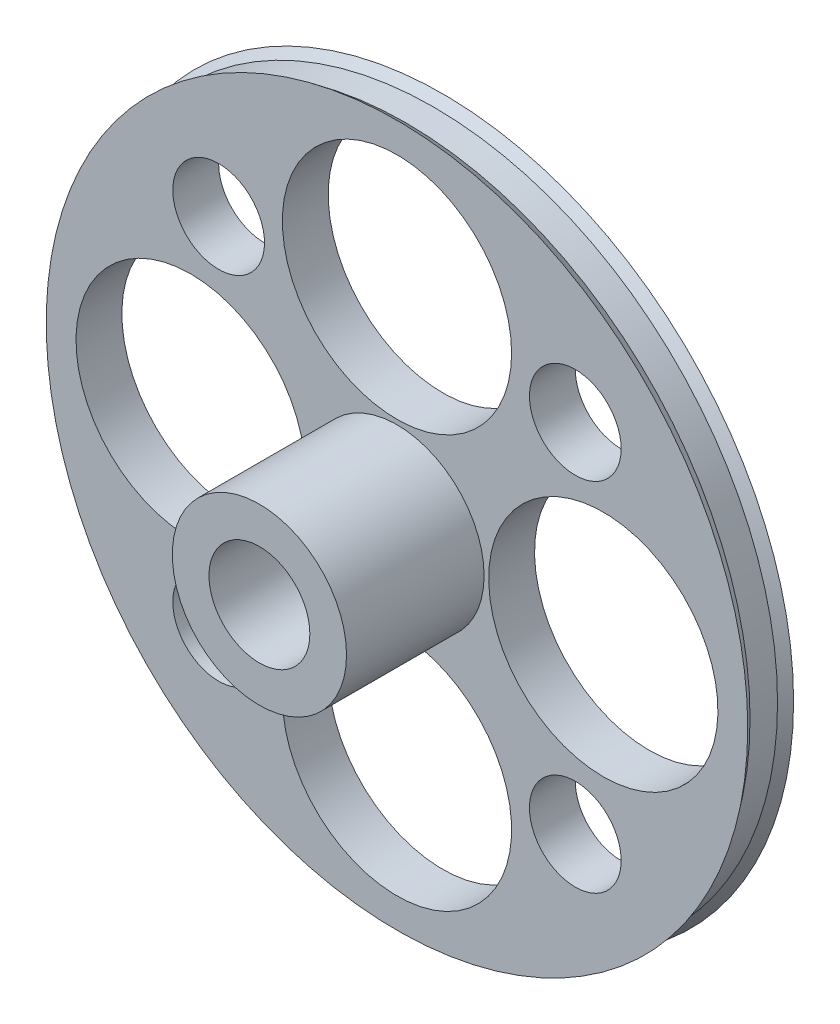
SolidWorks part; units mm, degrees
ref_plane "Front" through (0, 0, 0) normal (0, 0, 1) x (1, 0, 0)
ref_plane "Top" through (0, 0, 0) normal (0, 1, 0) x (1, 0, 0)
ref_plane "Right" through (0, 0, 0) normal (1, 0, 0) x (0, 0, -1)
sketch "Sketch1" plane through (0, 0, 0) normal (0, 0, 1) x (1, 0, 0)
  circle A0 centre (0, 0) radius 75
  dimension "D1" = 150
extrude "Boss-Extrude1" add sketch "Sketch1" along normal blind 10
sketch "Sketch2" plane through (0, 0, 10) normal (0, 0, 1) x (1, 0, 0)
  circle A0 centre (0, 0) radius 19
  dimension "D1" = 38
extrude "Boss-Extrude2" add sketch "Sketch2" along normal blind 30
sketch "Sketch3" plane through (0, 0, 40) normal (0, 0, 1) x (1, 0, 0)
  circle A0 centre (0, 0) radius 11
  dimension "D1" = 22
extrude "Cut-Extrude1" cut sketch "Sketch3" against normal through all
ref_axis "Axis1" through (0, 0, 40) along (0, 0, -1)
sketch "Sketch4" plane through (0, 0, 0) normal (0, 1, 0) x (1, 0, 0)
  line L0 (75, 0) -> (76.5, 0)
  line L1 (76.5, 0) -> (75, -2)
  line L2 (75, -10) -> (75, 0) construction
  line L3 (75, -2) -> (75, 0)
  line L4 (75, -10) -> (76.5, -10)
  line L5 (76.5, -10) -> (75, -8)
  line L6 (75, -8) -> (75, -10)
  dimension "D1" = 2
  dimension "D2" = 1.5
  dimension "D3" = 1.5
  dimension "D4" = 2
revolve "Revolve1" add sketch "Sketch4" angle 360 about axis through (0, 0, 40) along (0, 0, -1)
sketch "Sketch5" plane through (0, 0, 10) normal (0, 0, 1) x (1, 0, 0)
  circle A0 centre (0, 45) radius 25
  dimension "D1" = 50
  dimension "D2" = 45
extrude "Cut-Extrude2" cut sketch "Sketch5" against normal through all
pattern_circular "CirPattern1" count 4 over 360 about axis through (0, 0, 0) along (0, 0, 1) of "Cut-Extrude2"
sketch "Sketch6" plane through (0, 0, 10) normal (0, 0, 1) x (1, 0, 0)
  line L0 (0, 0) -> (38.8909, 38.8909) construction
  line L1 (0, 0) -> (0, 76.5) construction
  circle A0 centre (38.8909, 38.8909) radius 10
  circle A1 centre (0, 0) radius 76.5 construction
  dimension "D2" = 20
  dimension "D1" = 45
  dimension "D3" = 55
extrude "Cut-Extrude3" cut sketch "Sketch6" against normal through all
pattern_circular "CirPattern2" count 4 over 360 about axis through (0, 0, 0) along (0, 0, 1) of "Cut-Extrude3"
